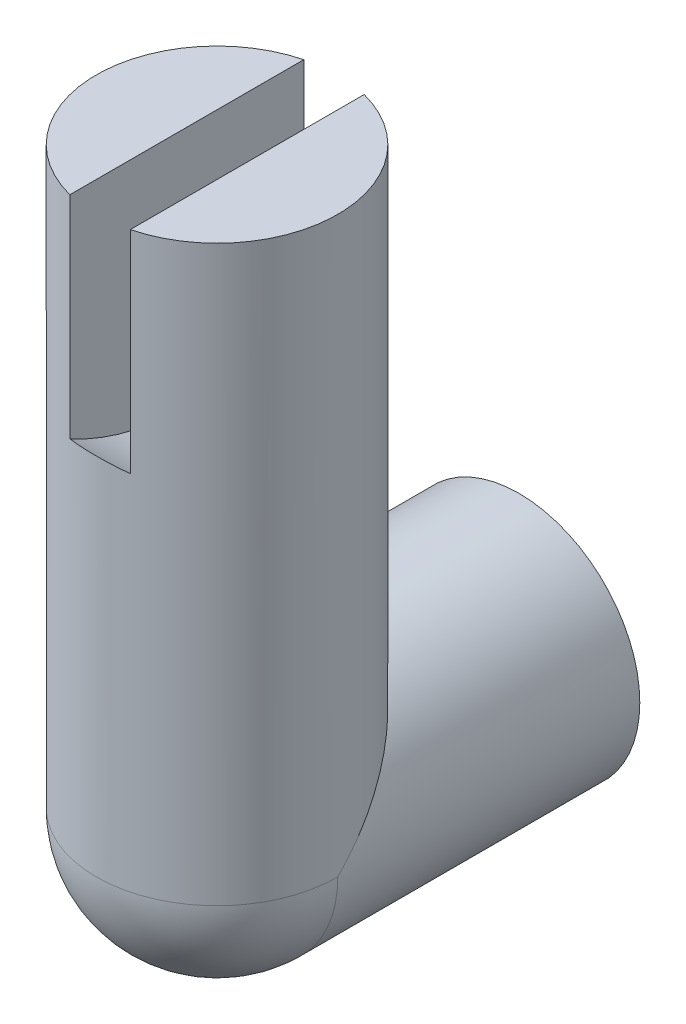
SolidWorks part; units mm, degrees
material "PLA-3d"
ref_plane "Alzado" through (0, 0, 0) normal (0, 0, 1) x (1, 0, 0)
ref_plane "Planta" through (0, 0, 0) normal (0, 1, 0) x (1, 0, 0)
ref_plane "Vista lateral" through (0, 0, 0) normal (1, 0, 0) x (0, 0, -1)
sketch "Croquis1" plane through (0, 0, 0) normal (0, 0, 1) x (1, 0, 0)
  circle A0 centre (0, 44.6491) radius 4
  dimension "D1" = 8
extrude "Saliente-Extruir1" add sketch "Croquis1" against normal blind 10 contours A0
sketch "Croquis2" plane through (0, 0, 0) normal (0, 0, 1) x (1, 0, 0)
  line L1 (-1, 38.1959) -> (1, 38.1959)
  line L2 (-1, 38.1959) -> (-1, 51.2557)
  line L3 (-1, 51.2557) -> (1, 51.2557)
  line L4 (1, 38.1959) -> (1, 51.2557)
  line L5 (-1, 38.1959) -> (1, 51.2557) construction
  line L6 (-1, 51.2557) -> (1, 38.1959) construction
  point P0 (0, 44.7258)
  dimension "D1" = 2
extrude "Cortar-Extruir1" [suppressed] cut sketch "Croquis2" against normal blind 6
sketch "Croquis3" plane through (0, 0, -10) normal (0, 0, -1) x (-1, 0, 0)
  circle A0 centre (0, 44.6491) radius 3
  dimension "D1" = 6
extrude "Cortar-Extruir2" cut sketch "Croquis3" against normal blind 5
sketch "Croquis4" plane through (0, 0, 0) normal (1, 0, 0) x (0, 0, -1)
  line L0 (0, 48.6491) -> (0, 40.6491) construction
  line L1 (0, 44.6491) -> (-4, 44.6491)
  line L2 (0, 44.6491) -> (0, 63.6491)
  line L3 (0, 63.6491) -> (-4, 63.6491)
  line L4 (-4, 44.6491) -> (-4, 63.6491)
  dimension "D1" = 4
  dimension "D2" = 19
revolve "Revolución1" add sketch "Croquis4" angle 360 about L2
sketch "Croquis5" plane through (0, 63.6491, 0) normal (0, 1, 0) x (1, 0, 0)
  line L0 (0, 0) -> (0, 7.4458) construction
  line L1 (1, 0) -> (-1, 0)
  line L2 (-1, 0) -> (-1, 8)
  line L3 (-1, 8) -> (1, 8)
  line L4 (1, 8) -> (1, 0)
  dimension "D1" = 2
  dimension "D2" = 8
revolve "Cortar-Revolución1" cut sketch "Croquis5" angle 360 about L1
sketch "Croquis6" plane through (0, 44.6491, 0) normal (0, -1, 0) x (1, 0, 0)
  line L0 (-4, 0) -> (4, 0)
  arc A0 (4, 0) -> (-4, 0) centre (0, 0) ccw
revolve "Revolución3" add sketch "Croquis6" angle 360 about L0
